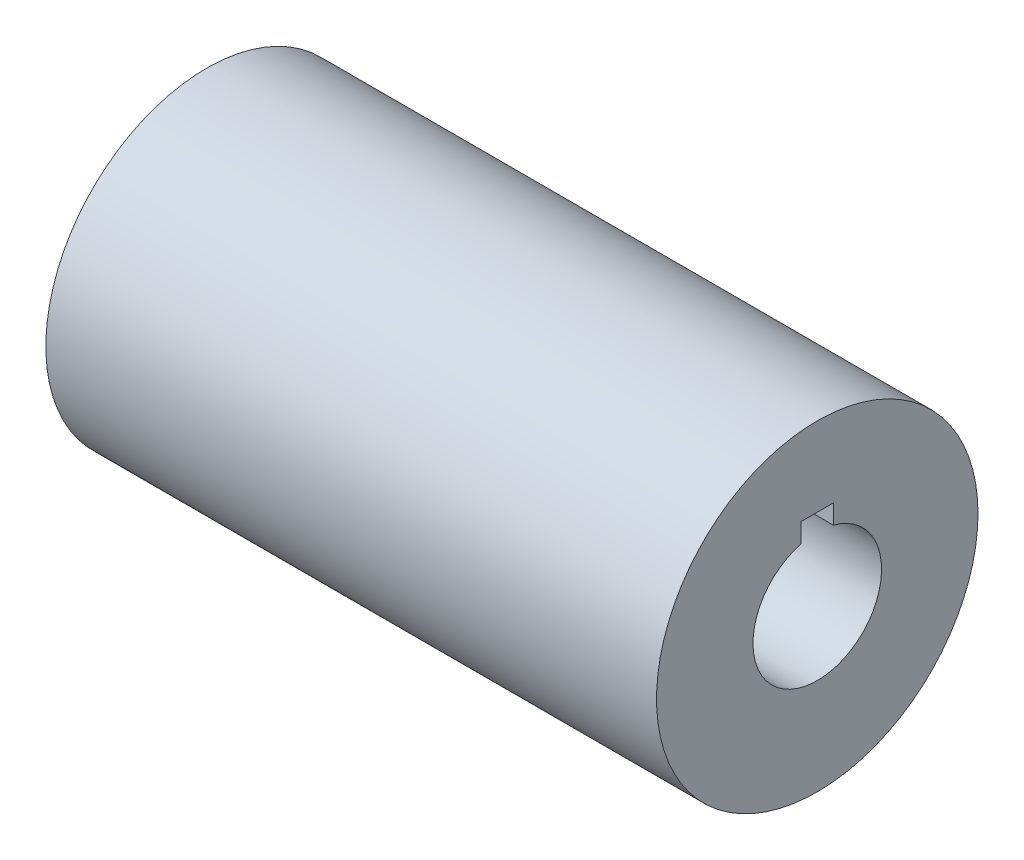
SolidWorks part; units mm, degrees
ref_plane "Front Plane" through (0, 0, 0) normal (0, 0, 1) x (1, 0, 0)
ref_plane "Top Plane" through (0, 0, 0) normal (0, 1, 0) x (1, 0, 0)
ref_plane "Right Plane" through (0, 0, 0) normal (1, 0, 0) x (0, 0, -1)
sketch "Sketch1" plane through (0, 0, 0) normal (1, 0, 0) x (0, 0, -1)
  circle A0 centre (0, 0) radius 10
extrude "Boss-Extrude2" add sketch "Sketch1" along normal blind 38 contours A0
sketch "Sketch9" plane through (38, 0, 0) normal (1, 0, 0) x (0, 0, -1)
  circle A0 centre (0, 0) radius 4
extrude "Cut-Extrude5" cut sketch "Sketch9" against normal blind 38
sketch "Sketch10" plane through (0, 0, 0) normal (-1, 0, 0) x (0, 0, 1)
  circle A0 centre (0, 0) radius 4.5
extrude "Cut-Extrude6" cut sketch "Sketch10" against normal blind 18
sketch "Sketch11" plane through (0, 0, 0) normal (-1, 0, 0) x (0, 0, 1)
  line L0 (0, 0) -> (0, 10.8746) construction
  line L2 (-1.5, 4.2426) -> (1.5, 4.2426)
  line L3 (-1.5, 4.2426) -> (-1.5, 5.8426)
  line L4 (-1.5, 5.8426) -> (1.5, 5.8426)
  line L5 (1.5, 4.2426) -> (1.5, 5.8426)
  circle A0 centre (0, 0) radius 4.5 construction
  dimension "D1" = 3
  dimension "D2" = 1.6
extrude "Cut-Extrude7" cut sketch "Sketch11" against normal blind 18
sketch "Sketch12" plane through (38, 0, 0) normal (1, 0, 0) x (0, 0, -1)
  line L0 (0, 0) -> (0, 10.7696) construction
  line L2 (-1, 3.873) -> (1, 3.873)
  line L3 (-1, 3.873) -> (-1, 5.073)
  line L4 (-1, 5.073) -> (1, 5.073)
  line L5 (1, 3.873) -> (1, 5.073)
  circle A0 centre (0, 0) radius 4 construction
  dimension "D1" = 2
  dimension "D2" = 1.2
extrude "Cut-Extrude8" cut sketch "Sketch12" against normal blind 20
